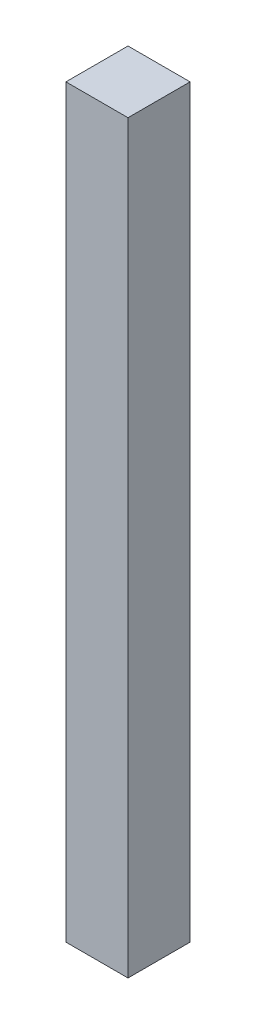
SolidWorks part; units mm, degrees
ref_plane "Front Plane" through (0, 0, 0) normal (0, 0, 1) x (1, 0, 0)
ref_plane "Top Plane" through (0, 0, 0) normal (0, 1, 0) x (1, 0, 0)
ref_plane "Right Plane" through (0, 0, 0) normal (1, 0, 0) x (0, 0, -1)
sketch "Sketch1" plane through (0, 0, 0) normal (0, 1, 0) x (1, 0, 0)
  line L1 (-14.6707, 4.9396) -> (10.7293, 4.9396)
  line L2 (-14.6707, 4.9396) -> (-14.6707, -20.4604)
  line L3 (-14.6707, -20.4604) -> (10.7293, -20.4604)
  line L4 (10.7293, 4.9396) -> (10.7293, -20.4604)
  dimension "D1" = 25.4
  dimension "D2" = 25.4
extrude "Boss-Extrude1" add sketch "Sketch1" along normal blind 304.8 contours L2 L1 L4 L3
